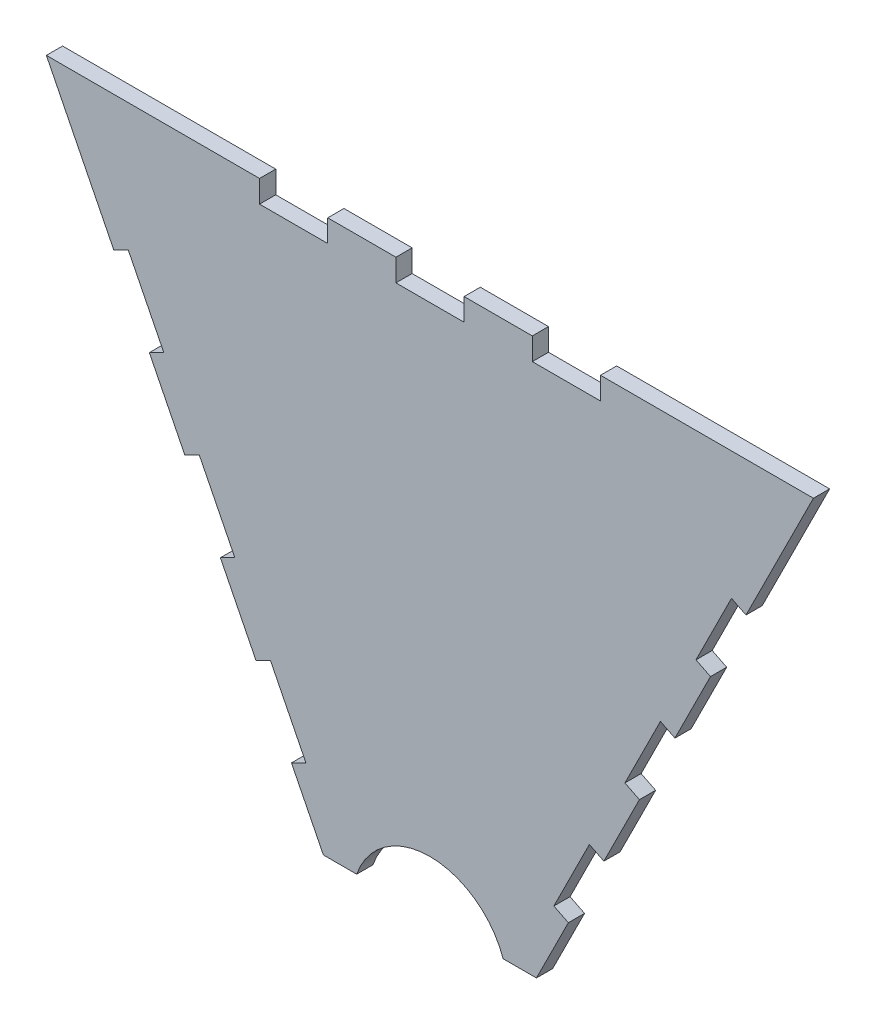
SolidWorks part; units mm, degrees
ref_plane "Front Plane" through (0, 0, 0) normal (0, 0, 1) x (1, 0, 0)
ref_plane "Top Plane" through (0, 0, 0) normal (0, 1, 0) x (1, 0, 0)
ref_plane "Right Plane" through (0, 0, 0) normal (1, 0, 0) x (0, 0, -1)
sketch "Sketch1" plane through (0, 0, 0) normal (0, 0, 1) x (1, 0, 0)
  line L0 (0, 165.1) -> (82.55, 0)
  line L1 (0, 0) -> (228.6, 0)
  line L2 (0, 0) -> (0, 165.1)
  line L3 (0, 165.1) -> (228.6, 165.1)
  line L4 (228.6, 0) -> (228.6, 165.1)
  line L6 (228.6, 165.1) -> (146.05, 0)
  dimension "D1" = 228.6
  dimension "D2" = 165.1
  dimension "D3" = 82.55
  dimension "D4" = 82.55
extrude "Boss-Extrude1" add sketch "Sketch1" along normal blind 4.826 contours L6 L3 L0 L1
sketch "Sketch2" plane through (0, 0, 4.826) normal (0, 0, 1) x (1, 0, 0)
  line L0 (114.3, 0) -> (114.3, 165.1) construction
  line L1 (20.0979, 124.9041) -> (24.4144, 127.0624)
  line L2 (0, 165.1) -> (82.55, 0) construction
  line L3 (24.4144, 127.0624) -> (35.003, 105.8853)
  line L4 (35.003, 105.8853) -> (30.6865, 103.7271)
  line L5 (30.6865, 103.7271) -> (20.0979, 124.9041)
  line L6 (41.275, 82.55) -> (45.5915, 84.7083)
  line L7 (45.5915, 84.7083) -> (56.18, 63.5312)
  line L8 (56.18, 63.5312) -> (51.8635, 61.3729)
  line L9 (51.8635, 61.3729) -> (41.275, 82.55)
  line L10 (62.4521, 40.1959) -> (66.7686, 42.3541)
  line L11 (66.7686, 42.3541) -> (77.3571, 21.1771)
  line L12 (77.3571, 21.1771) -> (73.0406, 19.0188)
  line L13 (73.0406, 19.0188) -> (62.4521, 40.1959)
  line L14 (0, 165.1) -> (228.6, 165.1) construction
  line L16 (35.003, 105.8853) -> (45.5915, 84.7083) construction
  line L17 (56.18, 63.5312) -> (66.7686, 42.3541) construction
  line L18 (77.3571, 21.1771) -> (87.9456, 0) construction
  line L19 (82.55, 0) -> (146.05, 0) construction
  line L20 (151.2429, 21.1771) -> (140.6544, 0) construction
  line L21 (172.42, 63.5312) -> (161.8314, 42.3541) construction
  line L22 (193.597, 105.8853) -> (183.0085, 84.7083) construction
  line L23 (155.5594, 19.0188) -> (166.1479, 40.1959)
  line L24 (151.2429, 21.1771) -> (155.5594, 19.0188)
  line L25 (161.8314, 42.3541) -> (151.2429, 21.1771)
  line L26 (166.1479, 40.1959) -> (161.8314, 42.3541)
  line L27 (176.7365, 61.3729) -> (187.325, 82.55)
  line L28 (172.42, 63.5312) -> (176.7365, 61.3729)
  line L29 (183.0085, 84.7083) -> (172.42, 63.5312)
  line L30 (187.325, 82.55) -> (183.0085, 84.7083)
  line L31 (197.9135, 103.7271) -> (208.5021, 124.9041)
  line L32 (193.597, 105.8853) -> (197.9135, 103.7271)
  line L33 (204.1856, 127.0624) -> (193.597, 105.8853)
  line L34 (208.5021, 124.9041) -> (204.1856, 127.0624)
  line L35 (77.3571, 21.1771) -> (87.9456, 0) construction
  dimension "D1" = 4.826
extrude "Cut-Extrude1" cut sketch "Sketch2" against normal through all
sketch "Sketch3" plane through (0, 0, 4.826) normal (0, 0, 1) x (1, 0, 0)
  line L0 (82.55, 0) -> (146.05, 0) construction
  line L2 (0, 165.1) -> (228.6, 165.1) construction
  circle A0 centre (114.3, -7.62) radius 23.114
  point P4 (114.3, 0)
  dimension "D1" = 46.228
  dimension "D2" = 172.72
  dimension "D3" = 0
extrude "Cut-Extrude2" cut sketch "Sketch3" against normal blind 4.826
sketch "Sketch4" plane through (0, 0, 4.826) normal (0, 0, 1) x (1, 0, 0)
  line L0 (165.1345, 163.2908) -> (144.8145, 163.2908) construction
  line L1 (144.8145, 167.908) -> (144.8145, 163.2908) construction
  line L2 (165.1345, 167.908) -> (165.1345, 163.2908) construction
  line L3 (165.1345, 167.908) -> (144.8145, 167.908) construction
  line L4 (124.4945, 167.908) -> (124.4945, 163.2908) construction
  line L5 (124.4945, 163.2908) -> (104.1745, 163.2908) construction
  line L6 (124.4945, 167.908) -> (104.1745, 167.908) construction
  line L7 (104.1745, 167.908) -> (104.1745, 163.2908) construction
  line L8 (83.8545, 167.908) -> (83.8545, 163.2908) construction
  line L9 (83.8545, 163.2908) -> (63.5345, 163.2908) construction
  line L10 (83.8545, 167.908) -> (63.5345, 167.908) construction
  line L11 (63.5345, 167.908) -> (63.5345, 163.2908) construction
  line L12 (165.1345, 163.2908) -> (144.8145, 163.2908)
  line L13 (144.8145, 167.908) -> (144.8145, 163.2908)
  line L14 (165.1345, 167.908) -> (165.1345, 163.2908)
  line L15 (165.1345, 167.908) -> (144.8145, 167.908)
  line L16 (124.4945, 167.908) -> (124.4945, 163.2908)
  line L17 (124.4945, 163.2908) -> (104.1745, 163.2908)
  line L18 (124.4945, 167.908) -> (104.1745, 167.908)
  line L19 (104.1745, 167.908) -> (104.1745, 163.2908)
  line L20 (83.8545, 167.908) -> (83.8545, 163.2908)
  line L21 (83.8545, 163.2908) -> (63.5345, 163.2908)
  line L22 (83.8545, 167.908) -> (63.5345, 167.908)
  line L23 (63.5345, 167.908) -> (63.5345, 163.2908)
extrude "Cut-Extrude3" cut sketch "Sketch4" against normal through all
sketch "Sketch5" plane through (0, 0, 4.826) normal (0, 0, 1) x (1, 0, 0)
  line L1 (165.1345, 163.2908) -> (144.8145, 163.2908)
  line L2 (165.1345, 163.2908) -> (165.1345, 158.4648)
  line L3 (165.1345, 158.4648) -> (144.8145, 158.4648)
  line L4 (144.8145, 163.2908) -> (144.8145, 158.4648)
  line L5 (124.4945, 163.2908) -> (104.1745, 163.2908)
  line L6 (124.4945, 163.2908) -> (124.4945, 158.4648)
  line L7 (124.4945, 158.4648) -> (104.1745, 158.4648)
  line L8 (104.1745, 163.2908) -> (104.1745, 158.4648)
  line L9 (83.8545, 163.2908) -> (63.5345, 163.2908)
  line L10 (83.8545, 163.2908) -> (83.8545, 158.4648)
  line L11 (83.8545, 158.4648) -> (63.5345, 158.4648)
  line L12 (63.5345, 163.2908) -> (63.5345, 158.4648)
  dimension "D1" = 4.826
extrude "Cut-Extrude4" cut sketch "Sketch5" against normal through all
equation "\"MDF\"= 0.19in"
equation "\"PVCID\" = 2.067in"
equation "\"PVCOD\" = 2.375in"
equation "\"GenDiameter\"= 60mm"
equation "\"GenCutDiameter\" = 1.8in"
equation "\"GenCutDistance\" = 1"
equation "\"TowerHeight\" = 6in"
equation "\"TowerFrontBase\" = 3in"
equation "\"FunnelHeight\" = 1in"
equation "\"FunnelAngle\" = 20"
equation "\"TowerSideBase\" = 3in"
equation "\"TowerPanelLength\" = 2in"
equation "\"TowerPanelLeeway\" = 0.5in"
equation "\"BaseLength\" = 9in"
equation "\"BaseWidth\" = 10in"
equation "\"WheelHoleLength\" = 3.25in"
equation "\"WheelHoleWidth\" = 26mm"
equation "\"WheelHoleFromBack\" = 1.5in"
equation "\"DropLength\" = 1in"
equation "\"DropWidth\" = 8.5in"
equation "\"BumperWidth\" = 2in"
equation "\"SmallHexDiameter\" = 0.185in"
equation "\"SmallHexHeight\" = 0.701in"
equation "\"ScrewSize\" = 0.106in"
equation "\"BigHexDiameter\" = 0.251in"
equation "\"BigHexHeight\" = 0.374in"
equation "\"PCBThickness\" = 0.066in"
equation "\"ConnectorHeight\" = 0.517in"
equation "\"BoardHeight\" = 0.583in"
equation "\"UnoStackHeight\" = 1.351in"
equation "\"UnoStackWidth\" = 3.053in"
equation "\"UnoStackLength\" = 3.152in"
equation "\"HBridgeWidth\" = 1.797in"
equation "\"HBridgeLength\" = 2.236in"
equation "\"DSWidth\" = 1.820in"
equation "\"DSLength\" = 1.833in"
equation "\"StepperWidth\" = 1.799in"
equation "\"StepperLength\" = 2.248in"
equation "\"ULNWidth\" = 1.304in"
equation "\"ULNLength\" = 1.545in"
equation "\"VSwitchHeight\" = 0.392in"
equation "\"VSwitchWidth\" = 0.637in"
equation "\"VSwitchLength\" = 1.097in"
equation "\"SkateWheelDiameter\" = 80mm"
equation "\"SkateWheelThickness\" = 24mm"
equation "\"BaseDistance\" = 3in"
equation "\"DummyVar\" = 2in"
equation "\"D1@Boss-Extrude1\"=\"MDF\""
equation "\"D1@Sketch2\"=\"MDF\""
equation "\"D1@Cut-Extrude2\"=\"MDF\""
equation "\"D1@Sketch5\"=\"MDF\""
